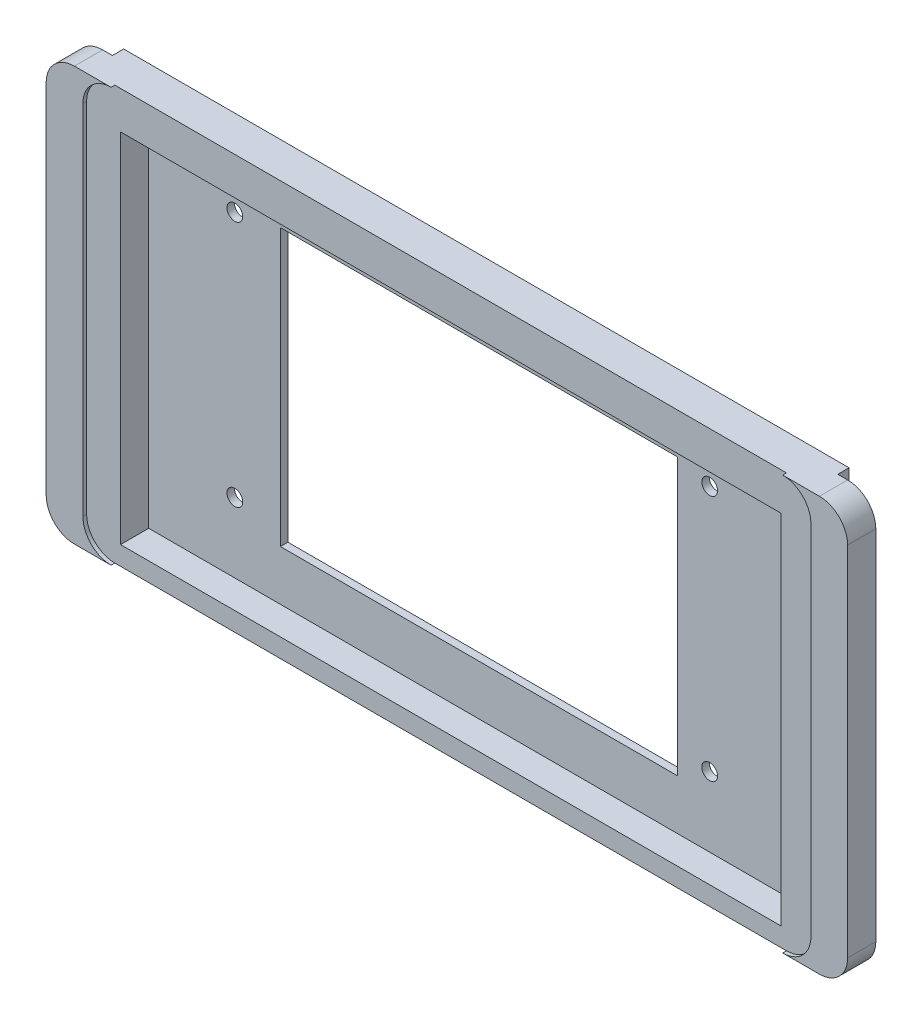
SolidWorks part; units mm, degrees
ref_plane "Front Plane" through (0, 0, 0) normal (0, 0, 1) x (1, 0, 0)
ref_plane "Top Plane" through (0, 0, 0) normal (0, 1, 0) x (1, 0, 0)
ref_plane "Right Plane" through (0, 0, 0) normal (1, 0, 0) x (0, 0, -1)
sketch "Sketch1" plane through (0, 0, 0) normal (0, 0, 1) x (1, 0, 0)
  line L1 (-99, 55) -> (99, 55)
  line L2 (-106.5, 47.5) -> (-106.5, -47.5)
  line L3 (-99, -55) -> (99, -55)
  line L4 (106.5, 47.5) -> (106.5, -47.5)
  line L5 (-106.5, 55) -> (106.5, -55) construction
  line L6 (-106.5, -55) -> (106.5, 55) construction
  arc A0 (-99, 55) -> (-106.5, 47.5) centre (-99, 47.5) ccw
  arc A1 (-106.5, -47.5) -> (-99, -55) centre (-99, -47.5) ccw
  arc A2 (99, -55) -> (106.5, -47.5) centre (99, -47.5) ccw
  arc A3 (99, 55) -> (106.5, 47.5) centre (99, 47.5) cw
  point P0 (0, 0)
  dimension "D3" = 7.5
  dimension "D1" = 213
  dimension "D2" = 110
extrude "Boss-Extrude1" add sketch "Sketch1" against normal blind 10.5
sketch "Sketch2" plane through (0, 0, 0) normal (0, 0, 1) x (1, 0, 0)
  line L0 (-99, -55) -> (99, -55) construction
  line L1 (-89.25, 55) -> (89.25, 55)
  line L2 (-96.75, 47.5) -> (-96.75, -47.5)
  line L3 (-89.25, -55) -> (89.25, -55)
  line L4 (96.75, 47.5) -> (96.75, -47.5)
  line L5 (-96.75, 55) -> (96.75, -55) construction
  line L6 (-96.75, -55) -> (96.75, 55) construction
  arc A0 (-96.75, -47.5) -> (-89.25, -55) centre (-89.25, -47.5) ccw
  arc A1 (89.25, -55) -> (96.75, -47.5) centre (89.25, -47.5) ccw
  arc A2 (89.25, 55) -> (96.75, 47.5) centre (89.25, 47.5) cw
  arc A3 (-89.25, 55) -> (-96.75, 47.5) centre (-89.25, 47.5) ccw
  point P0 (0, 0)
  dimension "D2" = 7.5
  dimension "D1" = 193.5
extrude "Cut-Extrude1" cut sketch "Sketch2" against normal blind 1
sketch "Sketch6" plane through (0, 0, -1) normal (0, 0, 1) x (1, 0, 0)
  line L0 (-89.25, -55) -> (89.25, -55) construction
  line L1 (-96.75, 47.5) -> (-96.75, -47.5) construction
  point P0 (-64.86, 34.2)
  point P2 (61.34, 34.2)
  point P4 (61.34, -31.45)
  point P6 (-64.86, -31.45)
  point P13 (0, 0)
  point P14 (0, 0)
  point P15 (0, 0)
  point P16 (0, 0)
  dimension "D1" = 23.55
  dimension "D2" = 65.65
  dimension "D3" = 126.2
  dimension "D4" = 31.89
hole_wizard "M5x0.8 Tapped Hole1" positions "Sketch6" profile "Sketch5" tap size "M5x0.8" standard "ANSI Metric"
sketch "Sketch5" plane through (-64.86, 34.2, -1) normal (1, 0, 0) x (0, -1, 0)
  line L0 (0, 0) -> (0, 13.6618)
  line L1 (0, 13.6618) -> (2.1, 12.4)
  line L2 (2.1, 12.4) -> (2.1, 0)
  line L5 (2.1, 0) -> (0, 0)
  line L10 (0, 13.6618) -> (-2.1, 12.4) construction
  line L11 (0, -6.35) -> (0, 107.95) construction
  dimension "Tap Drill Dia." = 4.2
  dimension "Tap Drill Depth" = 12.4
  dimension "Drill Angle" = 118
cosmetic thread "Hole Thread1" parameters "D1"=10, "D2"=5
cosmetic thread "Hole Thread2" parameters "D1"=10, "D2"=5
cosmetic thread "Hole Thread3" parameters "D1"=10, "D2"=5
cosmetic thread "Hole Thread4" parameters "D1"=10, "D2"=5
sketch "Sketch7" plane through (0, 0, -1) normal (0, 0, 1) x (1, 0, 0)
  line L1 (-52.76, -36.6995) -> (52.76, -36.6995)
  line L2 (-52.76, -36.6995) -> (-52.76, 36.6995)
  line L3 (-52.76, 36.6995) -> (52.76, 36.6995)
  line L4 (52.76, -36.6995) -> (52.76, 36.6995)
  line L5 (-52.76, -36.6995) -> (52.76, 36.6995) construction
  line L6 (-52.76, 36.6995) -> (52.76, -36.6995) construction
  circle A1 centre (-64.86, 34.2) radius 2.1 construction
  point P0 (0, 0)
  dimension "D2" = 10
extrude "Cut-Extrude2" cut sketch "Sketch7" against normal through all
sketch "Sketch9" plane through (0, 0, -1) normal (0, 0, 1) x (1, 0, 0)
  line L0 (-96.75, 47.5) -> (-96.75, -47.5) construction
  line L1 (-87.75, 45) -> (87.75, 45)
  line L2 (-87.75, 45) -> (-87.75, -50)
  line L3 (-87.75, -50) -> (87.75, -50)
  line L4 (87.75, 45) -> (87.75, -50)
  line L5 (96.75, -47.5) -> (96.75, 47.5) construction
  line L6 (-89.25, -55) -> (89.25, -55) construction
  line L7 (89.25, 55) -> (-89.25, 55) construction
  dimension "D1" = 9
  dimension "D2" = 9
  dimension "D3" = 5
  dimension "D4" = 10
extrude "Cut-Extrude3" cut sketch "Sketch9" against normal blind 7.5
sketch "Sketch10" plane through (0, 0, -10.5) normal (0, 0, -1) x (-1, 0, 0)
  line L1 (-99, 55) -> (99, 55) construction
  line L2 (-96.4, 55) -> (-99, 55)
  line L3 (-96.4, 55) -> (-96.4, -55)
  line L4 (-96.4, -55) -> (-99, -55)
  line L5 (-106.5, 47.5) -> (-106.5, -47.5)
  line L6 (99, -55) -> (-99, -55) construction
  line L7 (-106.5, -47.5) -> (-106.5, 47.5) construction
  line L8 (0, 5.775) -> (0, -5.775) construction
  line L9 (96.4, -55) -> (99, -55)
  line L10 (106.5, 47.5) -> (106.5, -47.5)
  line L11 (96.4, 55) -> (99, 55)
  line L12 (96.4, 55) -> (96.4, -55)
  arc A2 (-106.5, -47.5) -> (-99, -55) centre (-99, -47.5) ccw
  arc A3 (-106.5, 47.5) -> (-99, 55) centre (-99, 47.5) cw
  arc A4 (106.5, -47.5) -> (99, -55) centre (99, -47.5) cw
  arc A5 (106.5, 47.5) -> (99, 55) centre (99, 47.5) ccw
  point P14 (-106.5, 55)
  dimension "D2" = 7.5
  dimension "D1" = 10.1
extrude "Cut-Extrude4" cut sketch "Sketch10" against normal blind 3
